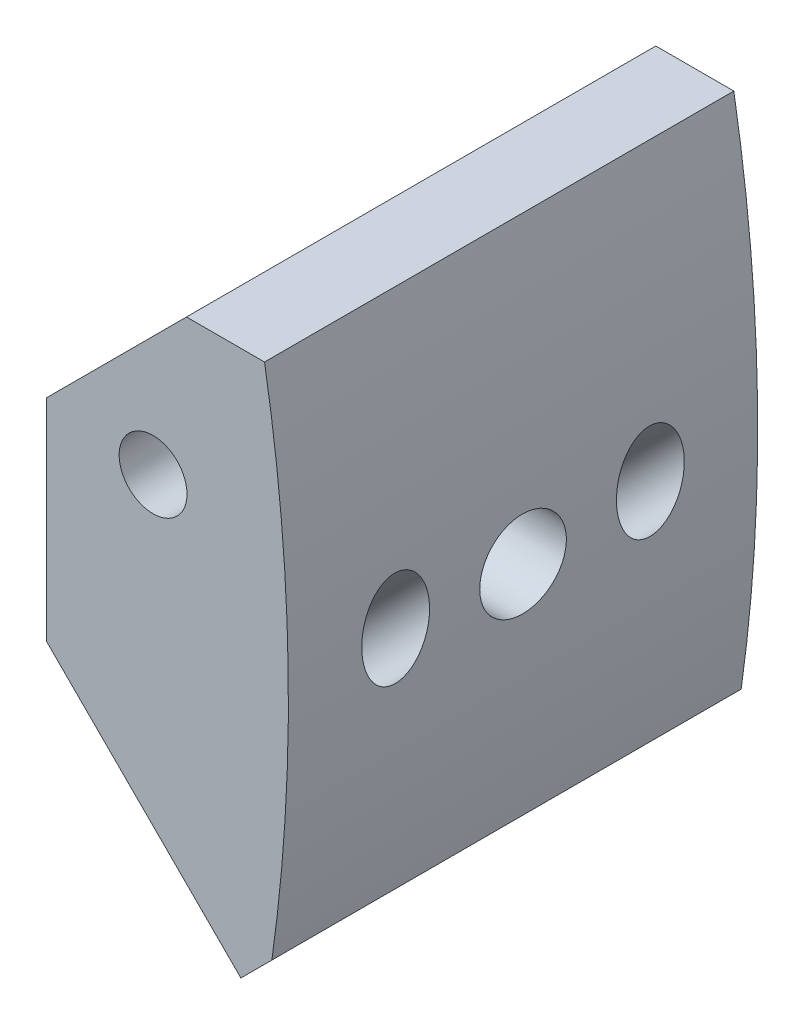
SolidWorks part; units mm, degrees
material "6061-T6 (SS)"
ref_plane "Front Plane" through (0, 0, 0) normal (0, 0, 1) x (1, 0, 0)
ref_plane "Top Plane" through (0, 0, 0) normal (0, 1, 0) x (1, 0, 0)
ref_plane "Right Plane" through (0, 0, 0) normal (1, 0, 0) x (0, 0, -1)
sketch "Sketch1" plane through (0, 0, 0) normal (0, 0, 1) x (1, 0, 0)
  line L0 (0, 0) -> (0, -13.1746)
  line L1 (0, -13.1746) -> (15.3242, -28.4988)
  line L2 (0, -6.5873) -> (15.3242, -6.5873) construction
  line L3 (15.3242, 15.3242) -> (0, 0) construction
  line L4 (15.3242, 15.3242) -> (15.3242, -6.5873) construction
  line L5 (15.3242, -6.5873) -> (15.3242, -28.4988) construction
  line L6 (19.05, -6.5873) -> (0, -6.5873) construction
  line L7 (0, 0) -> (0, 15.3242)
  line L8 (0, 15.3242) -> (15.3242, 15.3242)
  arc A0 (15.3242, 15.3242) -> (15.3242, -28.4988) centre (-47.244, -6.5873) cw
  dimension "D1" = 66.294
  dimension "D3" = 19.05
  dimension "D2" = 135
  dimension "D4" = 15.3242
extrude "Extrude1" add sketch "Sketch1" along normal blind 18.7198
sketch "Sketch23" plane through (0, 0, 0) normal (-1, 0, 0) x (0, 0, 1)
  line L0 (0, 0) -> (18.7198, 0) construction
  line L1 (18.7198, 15.3242) -> (18.7198, -13.1746) construction
  line L2 (9.3599, 0) -> (9.3599, -13.1746) construction
  line L3 (18.7198, -13.1746) -> (0, -13.1746) construction
  point P9 (9.3599, -6.5873)
sketch "Sketch2" plane through (0, 0, 0) normal (-1, 0, 0) x (0, 0, 1)
  line L0 (0, -6.5657) -> (18.7198, -6.5657) construction
  line L3 (9.3599, -13.1746) -> (9.3599, -6.5657) construction
  line L4 (18.7198, -13.1746) -> (0, -13.1746) construction
  point P6 (9.3599, -6.5657)
  dimension "D1" = 6.6089
sketch "Sketch13" plane through (0, 0, 18.7198) normal (0, 0, 1) x (1, 0, 0)
  line L0 (0, -13.1746) -> (0, 4.6054) construction
  line L1 (0, 4.6054) -> (30.3361, 4.6054)
  line L2 (0, 4.6054) -> (0, 31.0448)
  line L3 (0, 31.0448) -> (30.3361, 31.0448)
  line L4 (30.3361, 4.6054) -> (30.3361, 31.0448)
  dimension "D1" = 26.4394
  dimension "D2" = 30.3361
  dimension "D3" = 17.78
extrude "Extrude2" cut sketch "Sketch13" against normal through all
sketch "Sketch7" plane through (0, 0, 18.7198) normal (0, 0, 1) x (1, 0, 0)
  line L5 (19.05, -6.5873) -> (13.6525, -6.5873) construction
  line L6 (13.6525, -6.5873) -> (13.6525, -1.5073) construction
  arc A5 (15.3242, -28.4988) -> (18.0983, 4.6054) centre (-47.244, -6.5873) ccw construction
  dimension "D2" = 5.3975
  dimension "D4" = 5.08
hole_wizard "#6-32 Tapped Hole2" positions "Sketch9" profile "Sketch8" tap size "#6-32" standard "Ansi Inch" end condition through all
sketch "Sketch9" plane through (0, 0, 18.7198) normal (0, 0, 1) x (1, 0, 0)
  point P11 (13.6525, -1.5073)
sketch "Sketch8" plane through (13.6525, -1.5073, 18.7198) normal (1, 0, 0) x (0, -1, 0)
  line L0 (0, 0) -> (0, 18.7198)
  line L1 (0, 18.7198) -> (1.3525, 18.7198)
  line L2 (1.3525, 18.7198) -> (1.3525, 0)
  line L5 (1.3525, 0) -> (0, 0)
  line L11 (0, -6.35) -> (0, 107.95) construction
  dimension "Thru Tap Drill Dia." = 2.7051
  dimension "Thru Tap Drill Depth" = 18.7198
cosmetic thread "Hole Thread4" parameters "D2"=3.5052
sketch "Sketch10" plane through (-6.5873, -6.5873, 0) normal (-0.7071, -0.7071, 0) x (0.7071, -0.7071, 0)
  line L0 (30.9875, 9.3599) -> (18.5415, 9.3599) construction
  line L2 (18.5415, 9.3599) -> (18.5415, 16.9799) construction
  line L3 (18.5415, 9.3599) -> (18.5415, 1.7399) construction
  line L5 (30.9875, 18.7198) -> (30.9875, 0) construction
  dimension "D1" = 7.62
  dimension "D2" = 12.446
sketch "Sketch14" plane through (0, 0, 18.7198) normal (0, 0, 1) x (1, 0, 0)
  line L0 (0.6847, -13.8593) -> (7.2762, -7.2678)
  line L1 (0, -13.1746) -> (15.3242, -28.4988) construction
  line L2 (7.2762, -7.2678) -> (18.0525, -18.0441)
  line L3 (21.9157, -21.9073) -> (15.3242, -28.4988)
  line L4 (15.3242, -28.4988) -> (0.6847, -13.8593)
  line L5 (18.0525, -18.0441) -> (21.9157, -21.9073)
  arc A0 (15.3242, -28.4988) -> (18.0983, 4.6054) centre (-47.244, -6.5873) ccw construction
  dimension "D2" = 9.3218
  dimension "D3" = 15.24
extrude "Extrude3" cut sketch "Sketch14" against normal through all
sketch "Sketch16" plane through (0.0042, 0.0042, 0) normal (-0.7071, -0.7071, 0) x (0, 0, 1)
  line L2 (9.3599, -17.8863) -> (14.4399, -17.8863) construction
  line L3 (9.3599, -17.8863) -> (4.2799, -17.8863) construction
  line L4 (9.3599, -25.5242) -> (9.3599, -17.8863) construction
  line L5 (18.7198, -25.5242) -> (0, -25.5242) construction
  dimension "D1" = 10.16
  dimension "D3" = 7.6379
hole_wizard "#6-32 Tapped Hole1" positions "3DSketch1" profile "Sketch17" tap size "#6-32" standard "Ansi Inch" end condition through all
sketch3d "3DSketch1"
  point P0 (12.6517, -12.6433, 14.4399)
  point P8 (12.6517, -12.6433, 4.2799)
sketch "Sketch17" plane through (12.6517, -12.6433, 14.4399) normal (0, 0, 1) x (0.7071, -0.7071, 0)
  line L0 (0, 0) -> (0, 16.7209)
  line L1 (0, 16.7209) -> (1.3525, 16.7209)
  line L2 (1.3525, 16.7209) -> (1.3525, 0)
  line L5 (1.3525, 0) -> (0, 0)
  line L11 (0, -6.35) -> (0, 107.95) construction
  dimension "Thru Tap Drill Dia." = 2.7051
  dimension "Thru Tap Drill Depth" = 16.7209
cosmetic thread "Hole Thread1" parameters "D2"=3.5052
cosmetic thread "Hole Thread2" parameters "D2"=3.5052
hole_wizard "#8-32 Tapped Hole5" positions "Sketch26" profile "Sketch25" tap size "#8-32" standard "Ansi Inch"
sketch "Sketch26" plane through (0, 0, 0) normal (-1, 0, 0) x (0, 0, 1)
  point P1 (9.3599, -6.5873)
sketch "Sketch25" plane through (0, -6.5873, 9.3599) normal (0, 1, 0) x (0, 0, 1)
  line L0 (0, 0) -> (0, 20.0878)
  line L1 (0, 20.0878) -> (1.7272, 19.05)
  line L2 (1.7272, 19.05) -> (1.7272, 0)
  line L5 (1.7272, 0) -> (0, 0)
  line L10 (0, 20.0878) -> (-1.7272, 19.05) construction
  line L11 (0, -6.35) -> (0, 107.95) construction
  dimension "Tap Drill Dia." = 3.4544
  dimension "Tap Drill Depth" = 19.05
  dimension "Drill Angle" = 118
cosmetic thread "Hole Thread3" parameters "D1"=8.382, "D2"=4.1656
sketch "Sketch22" plane through (0, 0, 18.7198) normal (0, 0, 1) x (1, 0, 0)
  line L1 (0, 4.6054) -> (9.398, 4.6054)
  line L2 (0, 4.6054) -> (0, -17.0846)
  line L3 (0, -17.0846) -> (9.398, -17.0846)
  line L4 (9.398, 4.6054) -> (9.398, -17.0846)
  dimension "D1" = 21.6901
  dimension "D2" = 9.398
extrude "Extrude4" cut sketch "Sketch22" against normal through all
chamfer "Chamfer1" distance 5.588 angle 45 1 edges at (9.398, 4.6054, 9.3599)
sketch "Sketch27" plane through (0, 0, 18.7198) normal (0, 0, 1) x (1, 0, 0)
  line L0 (17.1545, -17.1461) -> (21.888, -12.4125)
  line L1 (18.0525, -18.0441) -> (9.398, -9.3896) construction
  line L2 (17.1545, -17.1461) -> (18.0525, -18.0441)
  line L3 (18.0525, -18.0441) -> (22.7861, -13.3106)
  line L4 (22.7861, -13.3106) -> (21.888, -12.4125)
  dimension "D1" = 1.27
extrude "Cut-Extrude1" cut sketch "Sketch27" against normal through all
